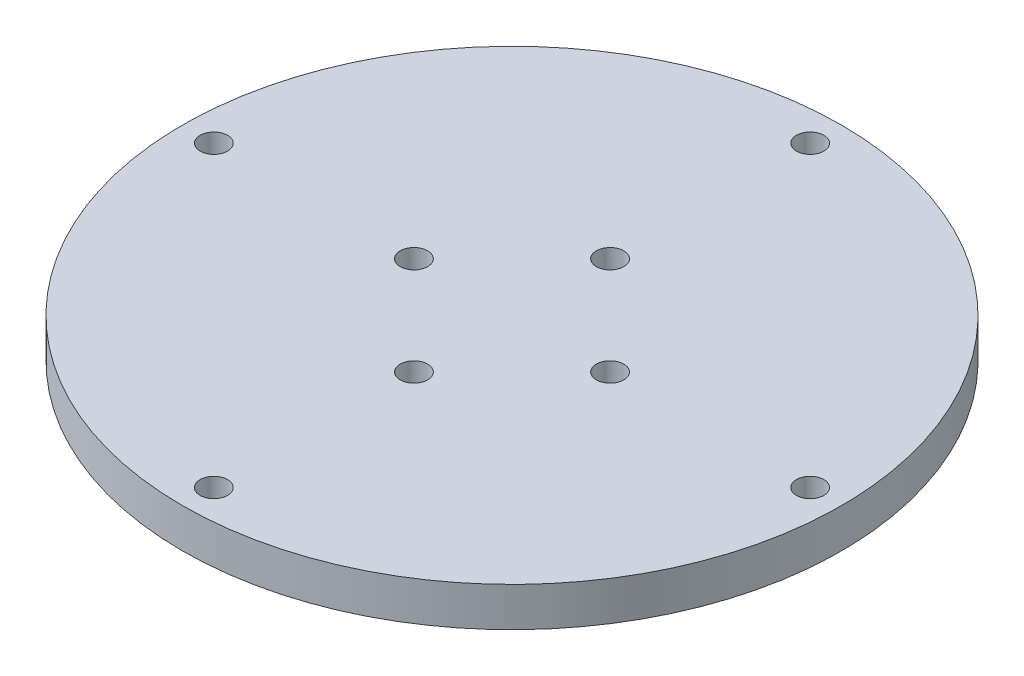
SolidWorks part; units mm, degrees
ref_plane "Front Plane" through (0, 0, 0) normal (0, 0, 1) x (1, 0, 0)
ref_plane "Top Plane" through (0, 0, 0) normal (0, 1, 0) x (1, 0, 0)
ref_plane "Right Plane" through (0, 0, 0) normal (1, 0, 0) x (0, 0, -1)
sketch "Sketch1" plane through (0, 0, 0) normal (0, 1, 0) x (1, 0, 0)
  circle A0 centre (0, 0) radius 84
  dimension "D1" = 168
extrude "Boss-Extrude1" add sketch "Sketch1" along normal blind 10
sketch "Sketch2" plane through (0, 10, 0) normal (0, 1, 0) x (1, 0, 0)
  circle A6 centre (0, 25) radius 4.0451
  circle A7 centre (-25, 0) radius 2.7082
  circle A8 centre (25, 0) radius 4.7247
  circle A9 centre (0, -25) radius 5.3373
  circle A11 centre (0, 76) radius 2.8249
  circle A12 centre (-76, 0) radius 3.769
  circle A13 centre (76, 0) radius 4.3482
  circle A14 centre (0, -76) radius 4.6016
hole_wizard "M6 Clearance Hole1" positions "3DSketch2" profile "Sketch4" hole size "M6" standard "ISO" end condition through all
sketch3d "3DSketch2"
  point P0 (0, 10, -76)
  point P3 (-76, 10, 0)
  point P6 (76, 10, 0)
  point P9 (25, 10, 0)
  point P12 (0, 10, -25)
  point P15 (-25, 10, 0)
  point P18 (0, 10, 25)
  point P21 (0, 10, 76)
sketch "Sketch4" plane through (0, 10, -76) normal (1, 0, 0) x (0, 0, 1)
  line L0 (0, 0) -> (0, 10)
  line L1 (0, 10) -> (3.5, 10)
  line L2 (3.5, 10) -> (3.5, 0)
  line L5 (3.5, 0) -> (0, 0)
  line L11 (0, -6.35) -> (0, 107.95) construction
  dimension "Thru Hole Dia." = 7
  dimension "Thru Hole Depth" = 10
